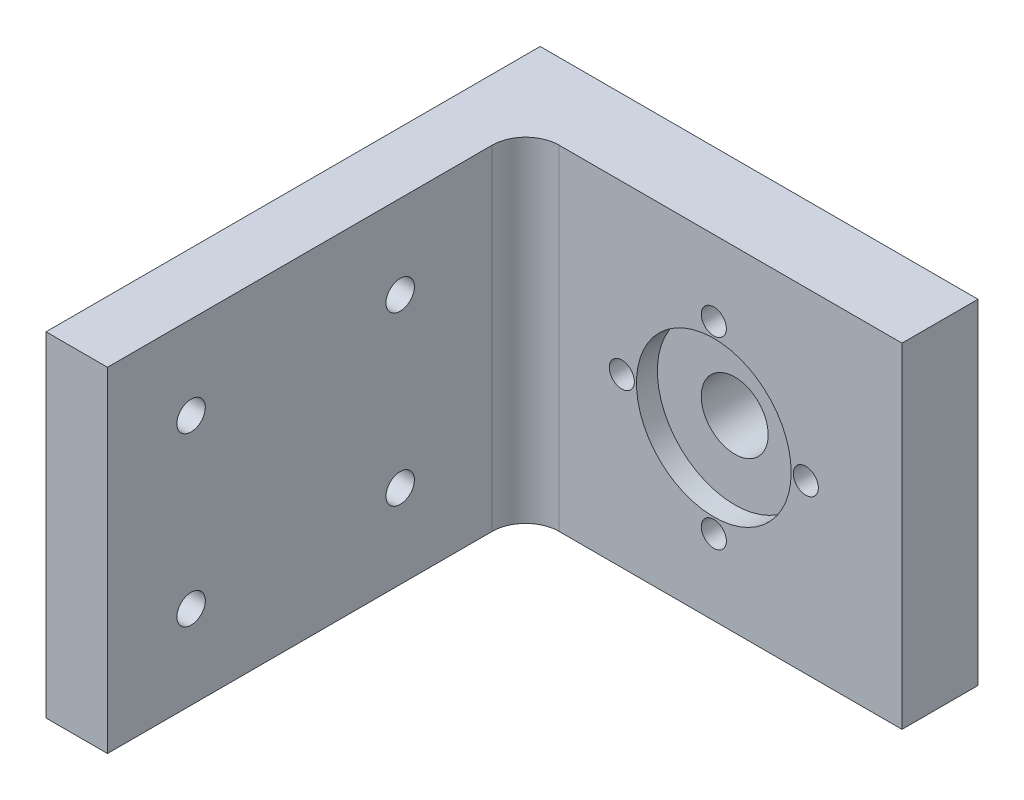
SolidWorks part; units mm, degrees
ref_plane "Front Plane" through (0, 0, 0) normal (1, 0, 0) x (0, 1, 0)
ref_plane "Top Plane" through (0, 0, 0) normal (0, 0, 1) x (0, 1, 0)
ref_plane "Right Plane" through (0, 0, 0) normal (0, 1, 0) x (-1, 0, 0)
sketch "Sketch1" plane through (0, 0, 0) normal (0, 0, 1) x (0, 1, 0)
  line L1 (-20, -22.5) -> (20, -22.5)
  line L2 (-20, -22.5) -> (-20, 22.5)
  line L3 (-20, 22.5) -> (20, 22.5)
  line L4 (20, -22.5) -> (20, 22.5)
  line L5 (-20, -22.5) -> (20, 22.5) construction
  line L6 (-20, 22.5) -> (20, -22.5) construction
  point P0 (0, 0)
  dimension "D1" = 45
  dimension "D2" = 40
extrude "Boss-Extrude1" add sketch "Sketch1" along normal blind 9.09 contours L3 L4 L1 L2
sketch "Sketch2" plane through (0, 0, 9.09) normal (0, 0, 1) x (1, 0, 0)
  line L0 (-22.5, 0) -> (22.5, 0) construction
  line L1 (-22.5, -20) -> (-22.5, 20) construction
  line L2 (22.5, -20) -> (22.5, 20) construction
  line L3 (0, 20) -> (0, -20) construction
  line L4 (22.5, 20) -> (-22.5, 20) construction
  line L5 (22.5, -20) -> (-22.5, -20) construction
  circle A0 centre (0, 0) radius 11 construction
  circle A1 centre (0, 11) radius 1.5
  circle A2 centre (11, 0) radius 1.5
  circle A3 centre (0, -11) radius 1.5
  circle A4 centre (-11, 0) radius 1.5
  dimension "D1" = 22
  dimension "D2" = 3
extrude "Cut-Extrude1" cut sketch "Sketch2" against normal through all
sketch "Sketch3" plane through (0, 0, 9.09) normal (0, 0, 1) x (1, 0, 0)
  line L0 (0, 20) -> (0, -20) construction
  line L1 (22.5, 20) -> (-22.5, 20) construction
  line L2 (22.5, -20) -> (-22.5, -20) construction
  line L3 (-22.5, 0) -> (22.5, 0) construction
  line L4 (-22.5, -20) -> (-22.5, 20) construction
  line L5 (22.5, -20) -> (22.5, 20) construction
  circle A0 centre (0, 0) radius 9.25
  dimension "D1" = 18.5
extrude "Cut-Extrude4" cut sketch "Sketch3" against normal blind 2.5
sketch "Sketch4" plane through (0, 0, 6.59) normal (0, 0, 1) x (1, 0, 0)
  circle A0 centre (0, 0) radius 4
  dimension "D1" = 8
extrude "Cut-Extrude5" cut sketch "Sketch4" against normal through all
sketch "Sketch5" plane through (-22.5, 0, 0) normal (-1, 0, 0) x (0, -1, 0)
  line L0 (20, 9.09) -> (20, 0) construction
  line L1 (-20, 0) -> (20, 0)
  line L2 (-20, 0) -> (-20, 59.09)
  line L3 (-20, 59.09) -> (20, 59.09)
  line L4 (20, 0) -> (20, 59.09)
  dimension "D1" = 59.09
extrude "Boss-Extrude2" add sketch "Sketch5" along normal blind 7.35
sketch "Sketch6" plane through (-22.5, 0, 0) normal (1, 0, 0) x (0, 1, 0)
  line L0 (-20, 24.09) -> (20, 24.09) construction
  line L1 (-20, 9.09) -> (-20, 59.09) construction
  line L2 (20, 59.09) -> (20, 9.09) construction
  line L3 (-20, 49.09) -> (20, 49.09) construction
  line L4 (-20, 9.09) -> (20, 9.09) construction
  line L5 (-10, 59.09) -> (-10, 9.09) construction
  line L6 (-20, 59.09) -> (20, 59.09) construction
  line L7 (10, 59.09) -> (10, 9.09) construction
  line L8 (-20, 9.09) -> (20, 9.09) construction
  circle A0 centre (-10, 49.09) radius 1.7
  circle A1 centre (10, 49.09) radius 1.7
  circle A2 centre (-10, 24.09) radius 1.7
  circle A3 centre (10, 24.09) radius 1.7
  dimension "D5" = 3.4
  dimension "D1" = 15
  dimension "D2" = 40
  dimension "D3" = 10
  dimension "D4" = 10
extrude "Cut-Extrude6" cut sketch "Sketch6" against normal through all
fillet "Fillet1" radius 4 1 edges at (-22.5, 0, 9.09)
equation "\"p\"= 300"
equation "\"a\"= 16"
equation "\"M\"= \"p\" * \"a\""
equation "\"Sy\"= 40"
equation "\"n\"= 3"
equation "\"E\"= 2000"
equation "\"delta\"= 0.3"
equation "\"b\"= 40"
equation "\"L1\"= 25"
equation "\"L2\"= 15"
equation "\"h1s\"= sqr ( 6 * \"M\" * \"n\" / ( \"b\" * \"Sy\" ) )"
equation "\"h1d\"= ( 6 * \"M\" * \"L1\" ^ 2 / ( \"E\" * \"b\" * \"delta\" ) ) ^ ( 1 / 3 )"
equation "\"h1\"= iif ( \"h1s\" > \"h1d\" , \"h1s\" , \"h1d\" )"
equation "\"h2s\"= sqr ( 6 * \"M\" * \"n\" / ( \"b\" * \"Sy\" ) )"
equation "\"h2d\"= ( 6 * \"M\" * \"L2\" ^ 2 / ( \"E\" * \"b\" * \"delta\" ) ) ^ ( 1 / 3 )"
equation "\"h2\"= iif ( \"h2s\" > \"h2d\" , \"h2s\" , \"h2d\" )"
